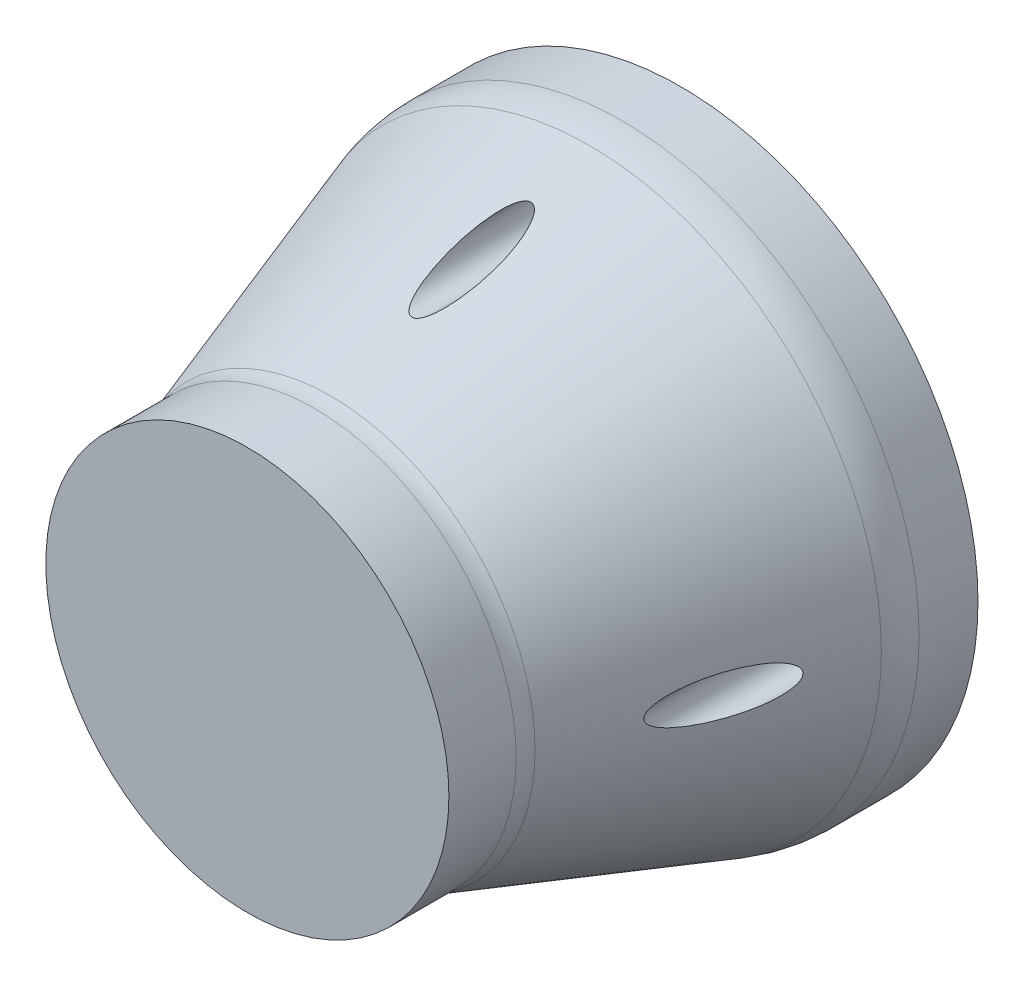
SolidWorks part; units mm, degrees
ref_plane "Front Plane" through (0, 0, 0) normal (0, 0, 1) x (1, 0, 0)
ref_plane "Top Plane" through (0, 0, 0) normal (0, 1, 0) x (1, 0, 0)
ref_plane "Right Plane" through (0, 0, 0) normal (1, 0, 0) x (0, 0, -1)
sketch "Sketch1" plane through (0, 0, 0) normal (0, 1, 0) x (1, 0, 0)
  line L0 (0, -171.1264) -> (0, 176.8465) construction
  line L1 (0, -43) -> (-40, -43)
  line L2 (-40, -43) -> (-40, -28)
  line L3 (-40, -28) -> (-59, 28)
  line L4 (-59, 28) -> (-59, 43)
  line L5 (-59, 43) -> (0, 43)
  line L6 (0, 0) -> (-41.6213, 0) construction
  line L7 (0, -43) -> (0, 43)
  dimension "D1" = 59
  dimension "D2" = 86
  dimension "D3" = 15
  dimension "D4" = 40
revolve "Revolve1" add sketch "Sketch1" angle 360 about L0
fillet "Fillet1" radius 20 1 edges at (59, 0, -28)
fillet "Fillet2" radius 10 1 edges at (40, 0, 28)
sketch "Sketch2" plane through (0, 0, 43) normal (0, 0, 1) x (1, 0, 0)
  circle A0 centre (0, 50) radius 4
  circle A1 centre (50, 0) radius 4
  circle A2 centre (0, -50) radius 4
  circle A3 centre (-50, 0) radius 4
  circle A4 centre (0, 0) radius 50 construction
  dimension "D1" = 100
  dimension "D2" = 8
extrude "Cut-Extrude1" cut sketch "Sketch2" against normal through all
sketch "Sketch3" plane through (0, 0, -43) normal (0, 0, -1) x (-1, 0, 0)
  point P0 (0, 0)
